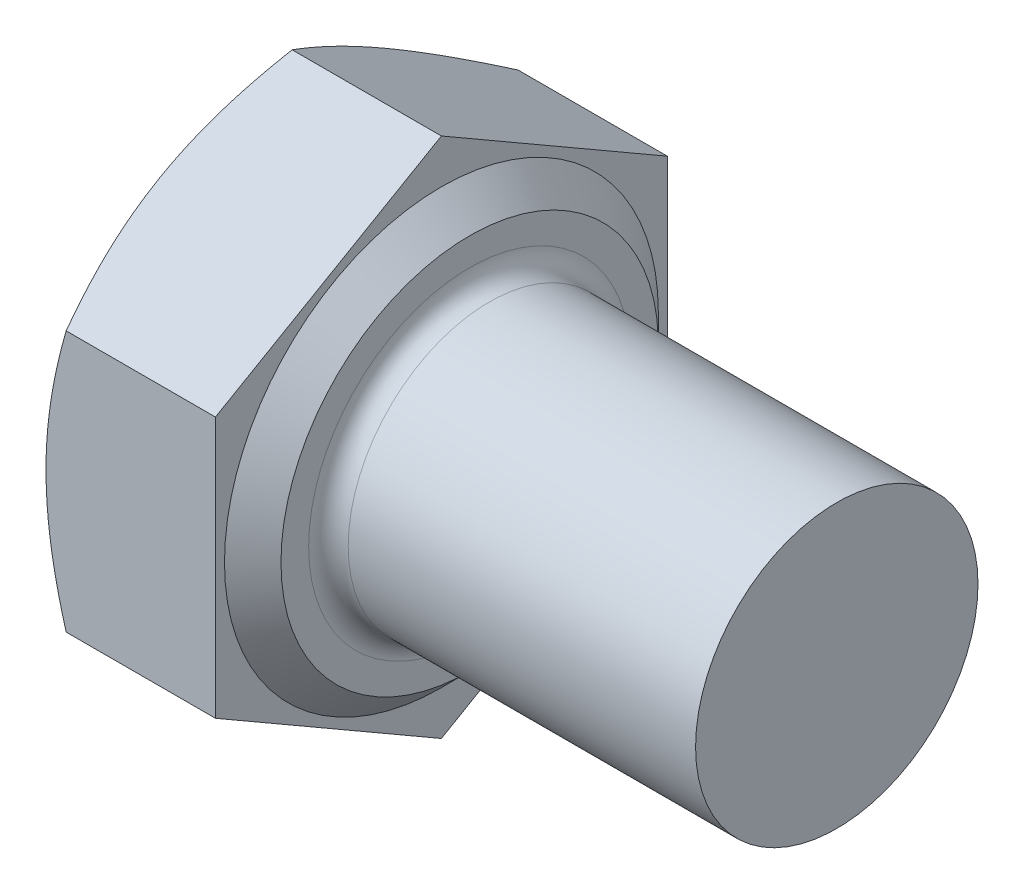
SolidWorks part; units mm, degrees
ref_plane "前视基准面" through (0, 0, 0) normal (0, 0, 1) x (1, 0, 0)
ref_plane "上视基准面" through (0, 0, 0) normal (0, 1, 0) x (1, 0, 0)
ref_plane "右视基准面" through (0, 0, 0) normal (1, 0, 0) x (0, 0, -1)
sketch "草图1" plane through (0, 0, 0) normal (0, 0, 1) x (1, 0, 0)
  line L0 (0, 0) -> (13.5, 0) construction
  line L1 (0, 0) -> (0, 4.395)
  line L2 (0, 4.395) -> (3.5, 4.395)
  line L3 (3.5, 4.395) -> (3.5, 0)
  line L4 (3.5, 2.5) -> (13.5, 2.5)
  line L5 (13.5, 2.5) -> (13.5, 0)
  line L6 (0, 4) -> (0.2281, 4.395)
  line L7 (12.3, 2.5) -> (12.3, 0)
  line L8 (5.9, 2.5) -> (5.9, 0)
  line L9 (3.5, 2.3051) -> (13.5, 2.3051)
  line L10 (13.5, 2.1752) -> (3.5, 2.1752)
  line L11 (3, 3.84) -> (3.5, 3.34)
  line L12 (3, 4.395) -> (3, 0)
  line L13 (3.4, 3.44) -> (3.4, 0) construction
  arc A0 (3.5, 2.85) -> (3.85, 2.5) centre (3.85, 2.85) ccw
  point P12 (12.9, 0)
  point P13 (1.15, 4.395)
  point P14 (3.5, 2.85)
  point P24 (3.5, 3.44)
  dimension "D1" = 0.1
  dimension "r" = 0.35
  dimension "k" = 3.5
  dimension "D2" = 45
  dimension "β" = 30
  dimension "e" = 8.79
  dimension "s" = 8
  dimension "d" = 5
  dimension "l" = 10
  dimension "D52" = 1.2
  dimension "P" = 0.6
  dimension "kw" = 2.35
  dimension "da" = 5.7
  dimension "a" = 2.4
  dimension "ds" = 4.6103
  dimension "D61" = 4.3505
  dimension "dw" = 6.88
  dimension "c" = 0.5
sketch "草图2" plane through (0, 0, 0) normal (1, 0, 0) x (0, 0, -1)
  line L1 (0, 4.6188) -> (-4, 2.3094)
  line L2 (-4, 2.3094) -> (-4, -2.3094)
  line L3 (-4, -2.3094) -> (0, -4.6188)
  line L4 (0, -4.6188) -> (4, -2.3094)
  line L5 (4, -2.3094) -> (4, 2.3094)
  line L6 (4, 2.3094) -> (0, 4.6188)
  circle A0 centre (0, 0) radius 4 construction
sketch "草图3" plane through (0, 0, 0) normal (1, 0, 0) x (0, 0, -1)
  line L0 (4, 2.3094) -> (0, 4.6188) construction
  line L1 (0, 4.6188) -> (-4, 2.3094) construction
  line L2 (-4, 2.3094) -> (-4, -2.3094) construction
  line L3 (4, -2.3094) -> (4, 2.3094) construction
  line L4 (0, -4.6188) -> (4, -2.3094) construction
  line L5 (-4, -2.3094) -> (0, -4.6188) construction
  line L6 (4, 2.3094) -> (0, 4.6188)
  line L7 (0, 4.6188) -> (-4, 2.3094)
  line L8 (-4, 2.3094) -> (-4, -2.3094)
  line L9 (4, -2.3094) -> (4, 2.3094)
  line L10 (0, -4.6188) -> (4, -2.3094)
  line L11 (-4, -2.3094) -> (0, -4.6188)
extrude "凸台-拉伸1" add sketch "草图3" along normal up to vertex (3.5 mm away) up to point (3.5, 4.395, 0)
sketch "草图4" plane through (0, 0, 0) normal (-1, 0, 0) x (0, 0, 1)
  circle A0 centre (0, 0) radius 4 construction
  circle A1 centre (0, 0) radius 4
  circle A2 centre (0, 0) radius 8.79
  dimension "D1" = 17.58
extrude "切除-拉伸1" cut sketch "草图4" against normal blind 0.4375 draft 60
sketch "草图5" plane through (0, 0, 0) normal (0, 0, 1) x (1, 0, 0)
  line L0 (3.5, 2.5) -> (13.5, 2.5) construction
  line L1 (13.5, 2.5) -> (13.5, 0) construction
  line L2 (0, 0) -> (13.5, 0) construction
  line L3 (3.85, 2.5) -> (13.5, 2.5)
  line L4 (13.5, 2.5) -> (13.5, 0)
  line L5 (3.5, 0) -> (13.5, 0)
  line L6 (3.5, 2.85) -> (3.5, 0)
  arc A0 (3.5, 2.85) -> (3.85, 2.5) centre (3.85, 2.85) ccw construction
  arc A1 (3.5, 2.85) -> (3.85, 2.5) centre (3.85, 2.85) ccw
revolve "旋转1" add sketch "草图5" angle 360 about L5
cosmetic thread "装饰螺纹线2" parameters "D1"=4.1, "D2"=4.3505
chamfer "倒角2" distance 0.2778 angle 45 1 edges at (13.5, 0, 2.5)
sketch "草图7" plane through (0, 0, 0) normal (0, 0, 1) x (1, 0, 0)
  line L0 (3.5, 3.34) -> (3, 3.84)
  line L1 (3, 3.84) -> (3, 8.79)
  line L2 (3, 8.79) -> (3.5, 8.79)
  line L3 (3.5, 8.79) -> (3.5, 3.34)
  line L4 (0, 0) -> (13.5, 0) construction
  line L5 (0, 0) -> (13.5, 0) construction
  dimension "D1" = 17.58
revolve "切除-旋转1" cut sketch "草图7" angle 360 mid plane about L5
sketch "草图6" [suppressed] plane through (0, 0, 0) normal (0, 0, 1) x (1, 0, 0)
  line L0 (9.3, 0) -> (9.3, 4) construction
  line L1 (9.3, 4) -> (75.3, 4)
  line L2 (75.3, 4) -> (75.3, 0)
  line L3 (9.3, 4) -> (5.9719, 3.5984)
  line L5 (5.3, 3.5941) -> (75.3, 3.5941) construction
  line L6 (5.3, 7.19) -> (5.3, 0) construction
  line L7 (5.3, 4.1941) -> (5.3, 0)
  line L8 (5.3, 0) -> (75.3, 0)
  arc A0 (5.9719, 3.5984) -> (5.3, 4.1941) centre (5.9, 4.1941) cw
  arc A1 (5.3, 4.6) -> (5.9, 4) centre (5.9, 4.6) ccw construction
revolve "旋转2" [suppressed] add sketch "草图6" angle 360 about L8
cosmetic thread "装饰螺纹线1" [suppressed] parameters "D1"=7.6, "D2"=4.3505
chamfer "倒角1" [suppressed] distance 0.2778 angle 45
sketch "草图8" [suppressed] plane through (0, 0, 0) normal (0, 0, 1) x (1, 0, 0)
  line L0 (5.3, 5.715) -> (4.7, 6.315)
  line L1 (4.7, 6.315) -> (4.7, 14.38)
  line L2 (4.7, 14.38) -> (5.3, 14.38)
  line L3 (5.3, 14.38) -> (5.3, 5.715)
  line L4 (0, 0) -> (75.3, 0) construction
  line L5 (0, 0) -> (75.3, 0) construction
  dimension "D1" = 17.58
revolve "切除-旋转2" [suppressed] cut sketch "草图8" angle 360 mid plane about L5
sketch "草图9" plane through (0, 0, 0) normal (0, 0, 1) x (1, 0, 0)
  line L0 (13.5, -2.2222) -> (13.5, 2.2222) construction
  line L1 (17, -2.5) -> (10, -2.5)
  line L2 (17, -2.5) -> (17, 2.5)
  line L3 (17, 2.5) -> (10, 2.5)
  line L4 (10, -2.5) -> (10, 2.5)
  line L5 (13.5, 2.5) -> (13.5, -2.5) construction
  line L6 (17, 0) -> (10, 0) construction
  line L7 (13.2222, 2.5) -> (3.85, 2.5) construction
  point P0 (13.5, 0)
  dimension "D1" = 7
extrude "切除-拉伸2" cut sketch "草图9" against normal mid plane 10
move or copy body "实体-移动/复制1" [suppressed] bodies to move or copy 105
